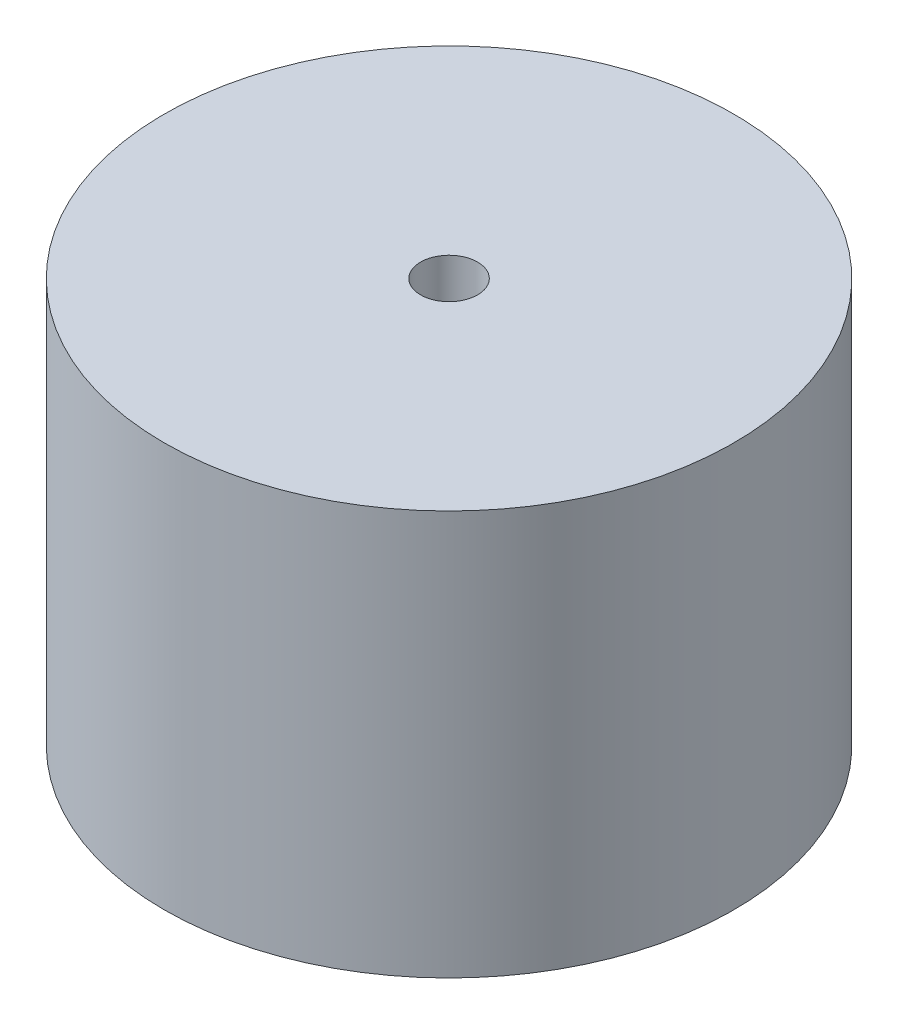
SolidWorks part; units mm, degrees
ref_plane "Front Plane" through (0, 0, 0) normal (0, 0, 1) x (1, 0, 0)
ref_plane "Top Plane" through (0, 0, 0) normal (0, 1, 0) x (1, 0, 0)
ref_plane "Right Plane" through (0, 0, 0) normal (1, 0, 0) x (0, 0, -1)
sketch "Sketch1" plane through (0, 0, 0) normal (0, 1, 0) x (1, 0, 0)
  circle A0 centre (0, 0) radius 12.7
  dimension "D1" = 25.4
extrude "Boss-Extrude1" add sketch "Sketch1" along normal blind 18.034
sketch "Sketch2" plane through (0, 18.034, 0) normal (0, 1, 0) x (1, 0, 0)
  circle A0 centre (0, 0) radius 1.27
  dimension "D1" = 2.54
extrude "Cut-Extrude1" cut sketch "Sketch2" against normal up to next
